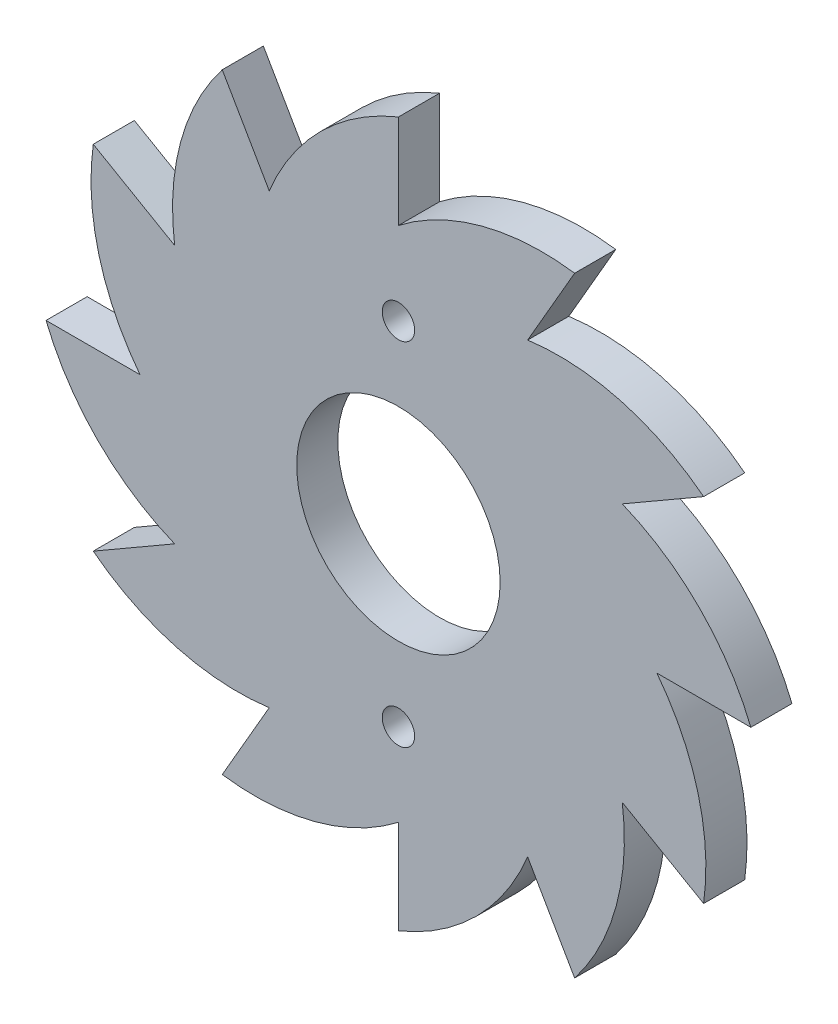
SolidWorks part; units mm, degrees
material "Cedar"
ref_plane "Front Plane" through (0, 0, 0) normal (0, 0, 1) x (1, 0, 0)
ref_plane "Top Plane" through (0, 0, 0) normal (0, 1, 0) x (1, 0, 0)
ref_plane "Right Plane" through (0, 0, 0) normal (1, 0, 0) x (0, 0, -1)
sketch "Sketch1" plane through (0, 0, 0) normal (0, 0, 1) x (1, 0, 0)
  circle A0 centre (0, 0) radius 38.1
  circle A1 centre (0, 18.9992) radius 1.7526
  circle A2 centre (0, 0) radius 10.9982
  circle A3 centre (0, -18.9992) radius 1.7526
  dimension "D1" = 76.2
  dimension "D2" = 3.5052
  dimension "D4" = 21.9964
  dimension "D5" = 3.5052
  dimension "D3" = 18.9992
  dimension "D6" = 18.9992
extrude "Boss-Extrude1" add sketch "Sketch1" along normal blind 4.445
sketch "Sketch3" plane through (0, 0, 4.445) normal (0, 0, 1) x (1, 0, 0)
  line L0 (0, 0) -> (0, 38.1)
  line L1 (0, 0) -> (-19.05, 32.9956)
  circle A0 centre (0, 0) radius 27.94
  circle A1 centre (0, 0) radius 38.1 construction
  arc A2 (-13.97, 24.1967) -> (0, 38.1) centre (9.5289, 14.5552) cw
  circle A3 centre (0, 0) radius 38.1
  point P3 (-13.97, 24.1967)
  circle M2 centre (0, 0) radius 38.1
  dimension "D1" = 55.88
  dimension "D3" = 25.4
  dimension "D2" = 30
extrude "Cut-Extrude1" cut sketch "Sketch3" against normal through all contours L1 A2 M2
pattern_circular "CirPattern1" count 12 every 30 about axis through (0, 0, 0) along (0, 0, 1) of "Cut-Extrude1"
